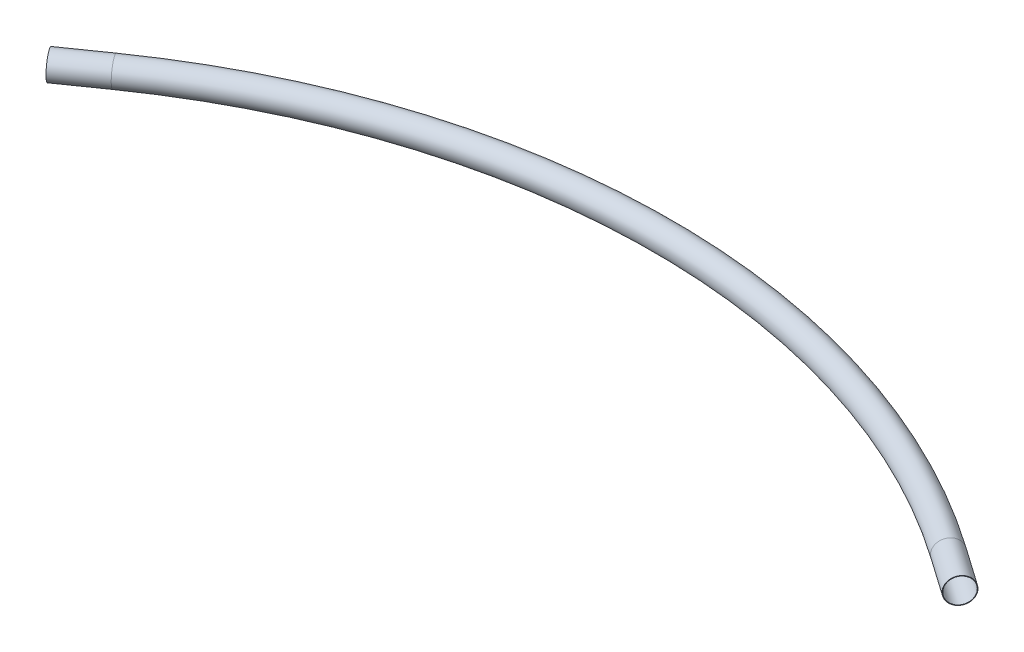
SolidWorks part; units mm, degrees
ref_plane "Front Plane" through (0, 0, 0) normal (0, 0, 1) x (1, 0, 0)
ref_plane "Top Plane" through (0, 0, 0) normal (0, 1, 0) x (1, 0, 0)
ref_plane "Right Plane" through (0, 0, 0) normal (1, 0, 0) x (0, 0, -1)
sketch "Sketch1" plane through (0, 0, 0) normal (0, 1, 0) x (1, 0, 0)
  line L0 (0, 0) -> (0, 855.6625) construction
  line L1 (-2714.625, 0) -> (2714.625, 0) construction
  line L2 (-2964.3325, -174.7833) -> (2964.3325, -174.7833) construction
  line L6 (-2714.625, 0) -> (-2964.3325, -174.7833)
  line L10 (2714.625, 0) -> (2964.3325, -174.7833)
  arc A1 (2714.625, 0) -> (-2714.625, 0) centre (0, -3878.2993) ccw
  dimension "D1" = 304.8
  dimension "D3" = 5429.25
  dimension "D2" = 855.6625
other "Structural Member1"
ref_plane "Plane1" through (2714.625, 0, 0) normal (-0.8193, 0, -0.5734) x (-0.5734, 0, 0.8193)
sketch "Sketch12" plane through (2714.625, 0, 0) normal (-0.8193, 0, -0.5734) x (-0.5734, 0, 0.8193)
  circle A0 centre (0, 0) radius 84.1375
  circle A1 centre (0, 0) radius 80.7339
  point P4 (0, 0)
  dimension "D1" = 168.275
  dimension "D2" = 161.4678
equation "\"D2@Sketch12\" = \"D1@Sketch12\" - .134*2"
